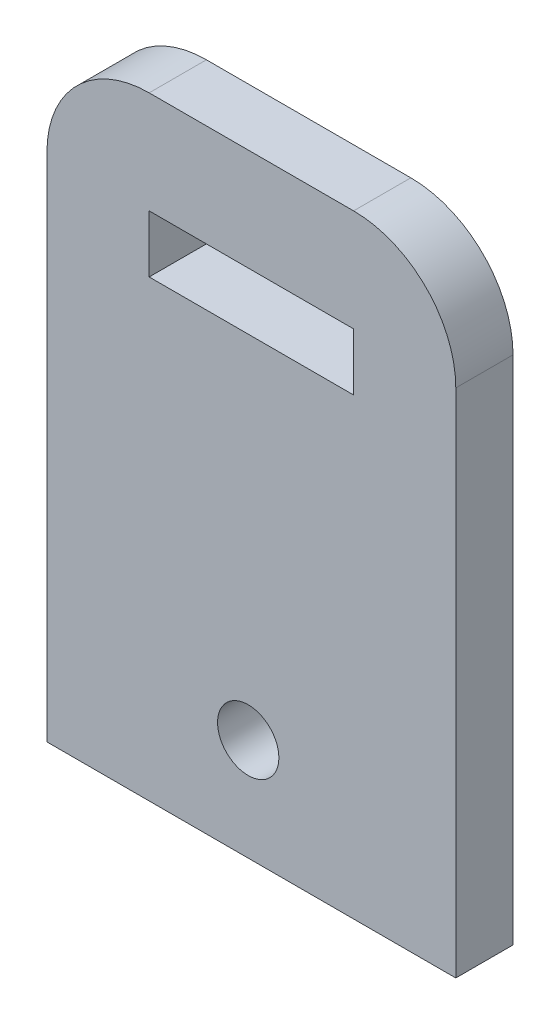
SolidWorks part; units mm, degrees
ref_plane "Front Plane" through (0, 0, 0) normal (0, 0, 1) x (1, 0, 0)
ref_plane "Top Plane" through (0, 0, 0) normal (0, 1, 0) x (1, 0, 0)
ref_plane "Right Plane" through (0, 0, 0) normal (1, 0, 0) x (0, 0, -1)
sketch "Model" plane through (0, 0, 0) normal (0, 0, 1) x (1, 0, 0)
  line L27 (91.882, -12.4275) -> (111.882, -12.4275)
  line L28 (111.882, -12.4275) -> (111.882, -2.4275)
  line L29 (106.882, 17.5725) -> (96.882, 17.5725)
  line L30 (91.882, 12.5725) -> (91.882, -2.4275)
  line L31 (101.882, 12.5725) -> (96.882, 12.5725)
  line L32 (96.882, 12.5725) -> (96.882, 9.7725)
  line L33 (96.882, 9.7725) -> (106.882, 9.7725)
  line L34 (106.882, 9.7725) -> (106.882, 12.5725)
  line L35 (106.882, 12.5725) -> (101.882, 12.5725)
  line L45 (91.882, -12.4275) -> (91.882, -2.4275)
  line L46 (111.882, -2.4275) -> (111.882, 12.5725)
  arc A89 (96.882, 17.5725) -> (91.882, 12.5725) centre (96.882, 12.5725) ccw
  arc A90 (111.882, 12.5725) -> (106.882, 17.5725) centre (106.882, 12.5725) ccw
  circle A91 centre (101.7273, -7.4275) radius 1.5
extrude "Boss-Extrude1" add sketch "Model" along normal blind 2.8
